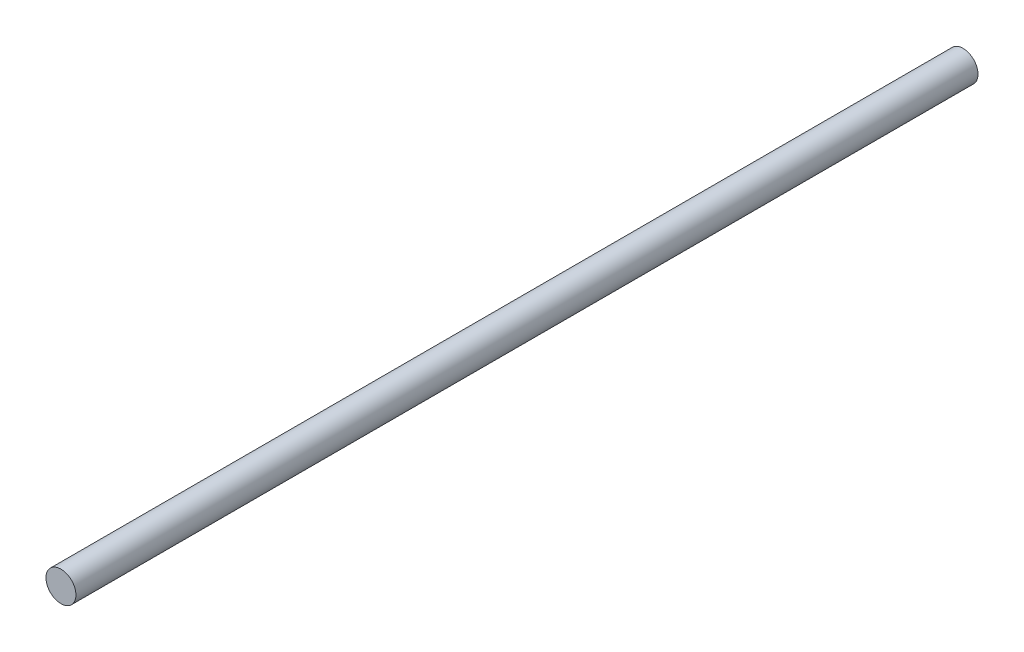
SolidWorks part; units mm, degrees
ref_plane "Front" through (0, 0, 0) normal (0, 0, 1) x (1, 0, 0)
ref_plane "Top" through (0, 0, 0) normal (0, 1, 0) x (1, 0, 0)
ref_plane "Right" through (0, 0, 0) normal (1, 0, 0) x (0, 0, -1)
sketch "Sketch1" plane through (0, 0, 0) normal (0, 0, 1) x (1, 0, 0)
  circle A0 centre (0, 0) radius 6.3246
  dimension "D1" = 12.6492
extrude "Boss-Extrude1" add sketch "Sketch1" along normal blind 381
